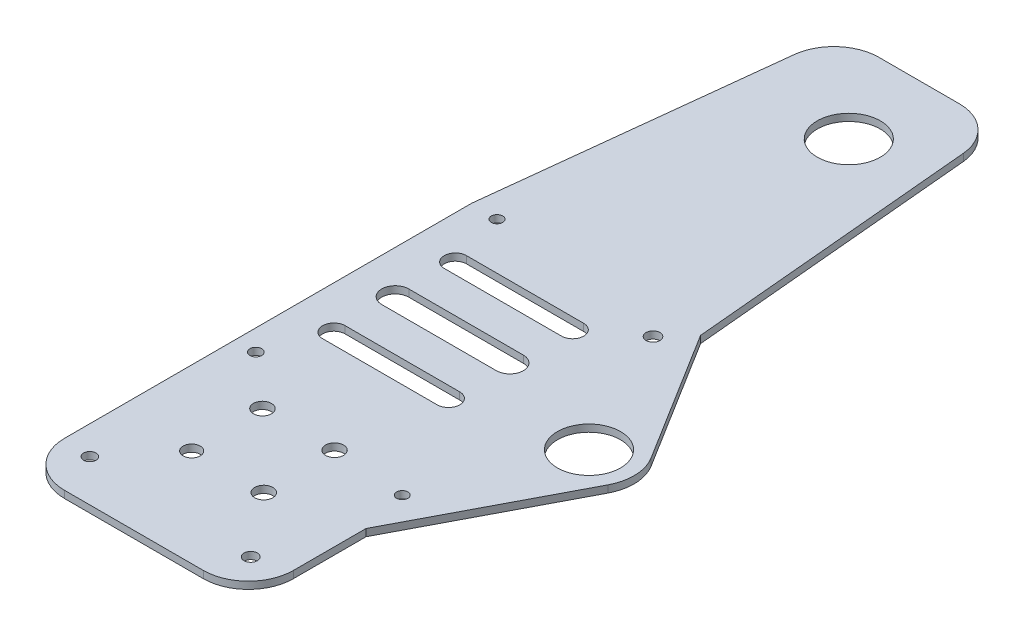
SolidWorks part; units mm, degrees
ref_plane "Front" through (0, 0, 0) normal (0, 0, 1) x (1, 0, 0)
ref_plane "Top" through (0, 0, 0) normal (0, 1, 0) x (1, 0, 0)
ref_plane "Right" through (0, 0, 0) normal (1, 0, 0) x (0, 0, -1)
sketch "Sketch1" plane through (0, 0, 0) normal (0, 1, 0) x (1, 0, 0)
  line L0 (10.4543, 228.6) -> (0, 135.3627)
  line L1 (0, 0) -> (50.8, 0)
  line L2 (0, 0) -> (0, 228.6)
  line L3 (0, 228.6) -> (50.8, 228.6)
  line L4 (50.8, 0) -> (50.8, 228.6)
  line L5 (42.3273, 228.6) -> (50.8, 135.3627)
  line L8 (50.8, 0) -> (24.327, 0)
  line L16 (50.8, 120.6192) -> (50.8, 104.4882)
  line L18 (50.8, 64.8791) -> (50.8, 87.4235)
  line L20 (9.492, 92.7849) -> (34.9257, 92.7849)
  line L21 (9.492, 92.7849) -> (9.492, 97.7849)
  line L22 (9.492, 97.7849) -> (34.9257, 97.7849)
  line L23 (34.9257, 92.7849) -> (34.9257, 97.7849)
  line L25 (9.492, 105.9099) -> (34.9257, 105.9099)
  line L26 (9.492, 105.9099) -> (9.492, 111.9099)
  line L27 (9.492, 111.9099) -> (34.9257, 111.9099)
  line L28 (34.9257, 105.9099) -> (34.9257, 111.9099)
  line L30 (9.492, 119.7849) -> (35.5097, 119.7849)
  line L31 (9.492, 119.7849) -> (9.492, 124.7158)
  line L32 (9.492, 124.7158) -> (35.5097, 124.7158)
  line L33 (35.5097, 119.7849) -> (35.5097, 124.7158)
  circle A12 centre (60.4, 101.001) radius 10
  circle A13 centre (29.5042, 189.5572) radius 7
  circle A22 centre (9.492, 95.2849) radius 2.5
  circle A23 centre (34.9257, 95.2849) radius 2.5
  circle A24 centre (34.9257, 108.9099) radius 3
  circle A25 centre (9.492, 108.9099) radius 3
  circle A26 centre (9.492, 122.2504) radius 2.4654
  circle A27 centre (35.5097, 122.2504) radius 2.4654
  circle A28 centre (16.5455, 56.6667) radius 1.897
  circle A29 centre (32.5429, 56.67) radius 2
  circle A30 centre (32.2518, 72.67) radius 2
  circle A31 centre (16.2545, 72.6667) radius 2
  circle A32 centre (43.4477, 42.8684) radius 1.4834
  circle A33 centre (6.3356, 44.2888) radius 1.3882
  circle A34 centre (4.6595, 82.7932) radius 1.3149
  circle A35 centre (48.401, 71.551) radius 1.2486
  circle A36 centre (45.7477, 129.8635) radius 1.5391
  circle A37 centre (5.8847, 135.1031) radius 1.2556
  point P10 (0, 0)
  dimension "D3" = 20
  dimension "D4" = 103.8842
  dimension "D5" = 16
  dimension "D6" = 14
  dimension "D7" = 116.6901
  dimension "D1" = 50.8
  dimension "D2" = 228.6
  dimension "D8" = 130.8151
  dimension "D9" = 56.6667
  dimension "D10" = 16
extrude "Boss-Extrude1" add sketch "Sketch1" along normal blind 1.5875 contours L1 L4 L3 L0 L2
sketch "Sketch4" plane through (0, 0, -228.6) normal (0, 0, -1) x (-1, 0, 0)
  line L1 (-61.3109, 11.9192) -> (4.9615, 11.9192)
  line L2 (-61.3109, 11.9192) -> (-61.3109, -15.8811)
  line L3 (-61.3109, -15.8811) -> (4.9615, -15.8811)
  line L4 (4.9615, 11.9192) -> (4.9615, -15.8811)
extrude "Cut-Extrude2" cut sketch "Sketch4" against normal blind 20
fillet "Fillet3" radius 10 1 edges at (44.1447, 0.7937, -208.6)
fillet "Fillet4" radius 10 3 edges at (50.8, 0.7937, 0) (0, 0.7937, 0) (8.2118, 0.7937, -208.6)
sketch "Sketch6" plane through (0, 1.5875, 0) normal (0, 1, 0) x (1, 0, 0)
  line L0 (68.8909, 106.2834) -> (50.8, 135.3627)
  line L1 (50.8, 135.3627) -> (50.8, 103.801)
  line L2 (69.2582, 96.3607) -> (50.8, 61.1242)
  line L3 (50.8, 10) -> (50.8, 98.201) construction
  line L4 (50.8, 61.1242) -> (50.8, 96.3607)
  line L5 (50.8, 96.3607) -> (50.8, 98.201)
  circle A0 centre (60.4, 101.001) radius 10
extrude "Boss-Extrude3" add sketch "Sketch6" against normal blind 1.5875
sketch "Sketch7" plane through (0, 1.5875, 0) normal (0, 1, 0) x (1, 0, 0)
  circle A0 centre (60.4, 101.001) radius 7
  dimension "D1" = 14
extrude "Cut-Extrude3" cut sketch "Sketch7" against normal blind 1.5875
sketch "Sketch8" plane through (0, 0, 0) normal (0, 0, 1) x (1, 0, 0)
  line L1 (-21.5979, 31.8127) -> (78.5082, 31.8127)
  line L2 (-21.5979, 31.8127) -> (-21.5979, -28.4046)
  line L3 (-21.5979, -28.4046) -> (78.5082, -28.4046)
  line L4 (78.5082, 31.8127) -> (78.5082, -28.4046)
extrude "Cut-Extrude4" cut sketch "Sketch8" against normal blind 35
fillet "Fillet5" radius 10 2 edges at (0, 0.7937, -35) (50.8, 0.7937, -35)
equation "\"7i\"=101.6"
